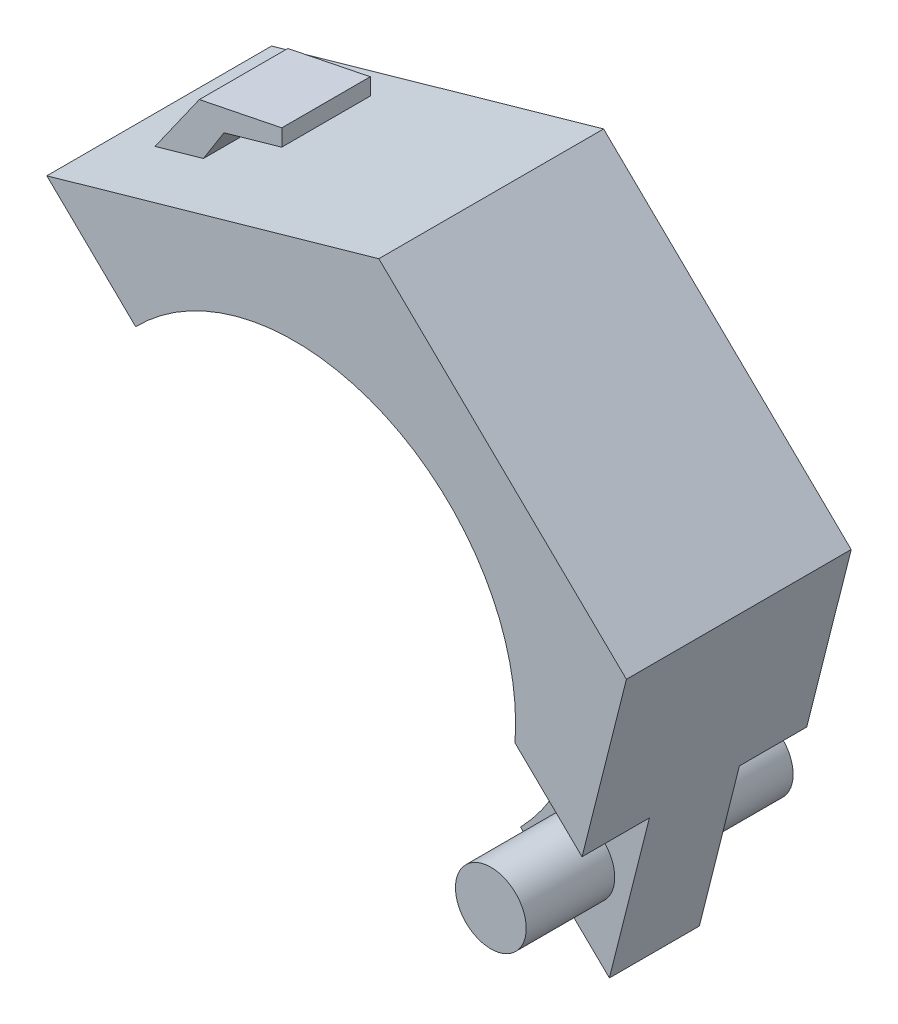
SolidWorks part; units mm, degrees
ref_plane "Front Plane" through (0, 0, 0) normal (0, 0, 1) x (1, 0, 0)
ref_plane "Top Plane" through (0, 0, 0) normal (0, 1, 0) x (1, 0, 0)
ref_plane "Right Plane" through (0, 0, 0) normal (1, 0, 0) x (0, 0, -1)
sketch "Sketch1" plane through (0, 0, 0) normal (0, 0, 1) x (1, 0, 0)
  line L0 (-27.9781, 27.1703) -> (27.9781, -27.1703)
  line L1 (27.9781, -27.1703) -> (37.5192, 10.6446)
  line L2 (37.5192, 10.6446) -> (9.5411, 37.8149)
  line L3 (9.5411, 37.8149) -> (-27.9781, 27.1703)
  line L8 (-32.7487, 8.2629) -> (-37.4713, -10.4545) [skipped]
  line L9 (-36.9478, -11.1995) -> (-23.0994, -24.6481) [skipped]
  line L10 (-8.7748, -37.5975) -> (9.7962, -32.3287) [skipped]
  arc A0 (17.9347, -17.4169) -> (-17.9347, 17.4169) centre (0, 0) ccw
  dimension "D1" = 50
  dimension "D2" = 14
extrude "Boss-Extrude1" add sketch "Sketch1" along normal blind 25.4 contours A0 L0 L1 L2 L3
sketch "Sketch2" plane through (0, 0, 25.4) normal (0, 0, 1) x (1, 0, 0)
  line L0 (21.4194, 1.5293) -> (45.0896, -21.4575)
  line L1 (17.9347, -17.4169) -> (27.9781, -27.1703) construction
  line L2 (21.4194, 1.5293) -> (5.3527, -38.6955)
  line L3 (5.3527, -38.6955) -> (45.0896, -21.4575)
extrude "Cut-Extrude1" cut sketch "Sketch2" against normal blind 7.62
sketch "Sketch3" plane through (0, 0, 17.78) normal (0, 0, 1) x (1, 0, 0)
  circle A0 centre (24.5789, -17.0231) radius 4
  dimension "D1" = 8
extrude "Boss-Extrude2" add sketch "Sketch3" along normal blind 10
ref_plane "Plane4" through (0, 0, 12.7) normal (0, 0, -1) x (-1, 0, 0)
mirror "Mirror1" about plane through (0, 0, 12.7) normal (0, 0, -1) of "Cut-Extrude1", "Boss-Extrude2"
sketch "Sketch4" plane through (0, 0, 12.7) normal (0, 0, -1) x (-1, 0, 0)
  line L0 (23.4511, 28.4547) -> (18.4428, 35.5477)
  line L1 (-9.5411, 37.8149) -> (27.9781, 27.1703) construction
  line L2 (18.4428, 35.5477) -> (9.1258, 37.439)
  line L3 (9.1258, 37.439) -> (9.1258, 35.5477)
  line L4 (9.1258, 35.5477) -> (15.6493, 33.6969)
  line L5 (15.6493, 33.6969) -> (17.9838, 30.0058)
  line L6 (17.9838, 30.0058) -> (23.4511, 28.4547)
extrude "Boss-Extrude3" add sketch "Sketch4" along normal mid plane 10
